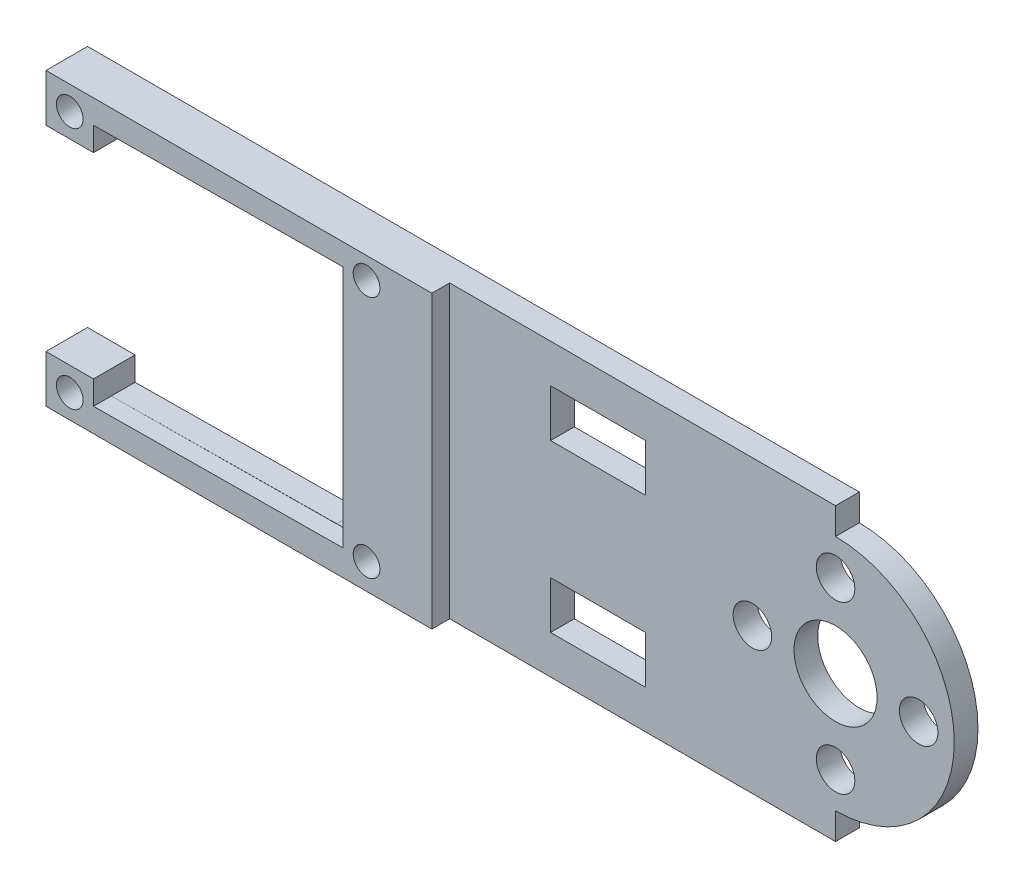
SolidWorks part; units mm, degrees
ref_plane "Front Plane" through (0, 0, 0) normal (0, 0, 1) x (1, 0, 0)
ref_plane "Top Plane" through (0, 0, 0) normal (0, 1, 0) x (1, 0, 0)
ref_plane "Right Plane" through (0, 0, 0) normal (1, 0, 0) x (0, 0, -1)
sketch "Sketch1" plane through (0, 0, 0) normal (0, 0, 1) x (1, 0, 0)
  line L6 (-27, -8.25) -> (-27, -12.25)
  line L12 (-27, 12.25) -> (38, 12.25)
  line L13 (38, 12.25) -> (38, 10)
  line L14 (38, -12.25) -> (-27, -12.25)
  line L16 (38, -10) -> (38, -12.25)
  line L17 (14, 9) -> (22, 9)
  line L18 (14, 9) -> (14, 5)
  line L19 (14, 5) -> (22, 5)
  line L20 (22, 9) -> (22, 5)
  line L21 (14, 9) -> (22, 5) construction
  line L22 (14, 5) -> (22, 9) construction
  line L23 (14, -5) -> (22, -5)
  line L24 (14, -5) -> (14, -9)
  line L25 (14, -9) -> (22, -9)
  line L26 (22, -5) -> (22, -9)
  line L27 (14, -5) -> (22, -9) construction
  line L28 (14, -9) -> (22, -5) construction
  line L44 (-27, 12.25) -> (-27, 8.25)
  line L45 (-27, 8.25) -> (-23, 8.25)
  line L46 (-23, 8.25) -> (-23, 10.25)
  line L51 (-23, -8.25) -> (-23, -10.25)
  line L53 (-23, 10.25) -> (-4.0014, 10.4292)
  line L54 (-4.0014, -10.0708) -> (-23, -10.25)
  line L55 (-27, -8.25) -> (-23, -8.25)
  line L56 (-4.0014, 10.4292) -> (-2, 10.4292)
  line L57 (-2, 10.4292) -> (-2, -10.0708)
  line L58 (-2, -10.0708) -> (-4.0014, -10.0708)
  arc A2 (38, -10) -> (38, 10) centre (38, 0) ccw
  circle A3 centre (38, 7) radius 1.625
  circle A4 centre (45, 0) radius 1.625
  circle A5 centre (38, -7) radius 1.625
  circle A6 centre (31, 0) radius 1.625
  circle A7 centre (38, 0) radius 3.5
  circle A10 centre (-25, 10.25) radius 1.125
  circle A11 centre (-25, -10.25) radius 1.125
  circle A12 centre (0, 10.4292) radius 1.125
  circle A13 centre (0, -10.0708) radius 1.125
  point P4 (0, 0)
  point P22 (18, 7)
  point P35 (18, -7)
  dimension "D4" = 2.25
  dimension "D11" = 20
  dimension "D12" = 3.25
  dimension "D15" = 7
  dimension "D30" = 2.25
  dimension "D31" = 4
  dimension "D6" = 2.25
  dimension "D7" = 2.25
  dimension "D8" = 2.25
  dimension "D17" = 0
  dimension "D5" = 2.25
  dimension "D9" = 2
  dimension "D10" = 4
  dimension "D13" = 7
  dimension "D16" = 2
  dimension "D18" = 2.0014
  dimension "D19" = 20
  dimension "D20" = 4
  dimension "D21" = 4
  dimension "D22" = 8
  dimension "D23" = 8
  dimension "D24" = 38
  dimension "D25" = 20.5
  dimension "D26" = 2
  dimension "D27" = 2
  dimension "D28" = 4
  dimension "D29" = 4
  dimension "D32" = 12.25
  dimension "D33" = 20.5
  dimension "D34" = 65
  dimension "D35" = 2
  dimension "D14" = 4
extrude "Boss-Extrude1" add sketch "Sketch1" along normal blind 2
sketch "Sketch8" plane through (0, 0, 2) normal (0, 0, 1) x (1, 0, 0)
  line L0 (-27, 12.25) -> (5.5, 12.25)
  line L1 (-27, 12.25) -> (38, 12.25) construction
  line L2 (5.5, 12.25) -> (5.5, -12.25)
  line L3 (38, -12.25) -> (-27, -12.25) construction
  line L4 (5.5, -12.25) -> (-27, -12.25)
  line L5 (-27, -12.25) -> (-27, -8.25)
  line L6 (-27, -8.25) -> (-23, -8.25)
  line L7 (-23, -8.25) -> (-23, -10.25)
  line L8 (-23, -10.25) -> (-2, -10.0708)
  line L9 (-2, -10.0708) -> (-2, 10.4292)
  line L10 (-2, 10.4292) -> (-23, 10.25)
  line L11 (-23, 10.25) -> (-23, 8.25)
  line L12 (-23, 8.25) -> (-27, 8.25)
  line L13 (-27, 8.25) -> (-27, 12.25)
  circle A0 centre (-25, 10.25) radius 1.125
  circle A1 centre (-25, -10.25) radius 1.125
  circle A2 centre (0, 10.4292) radius 1.125
  circle A3 centre (0, -10.0708) radius 1.125
extrude "Boss-Extrude4" add sketch "Sketch8" along normal blind 1.5
